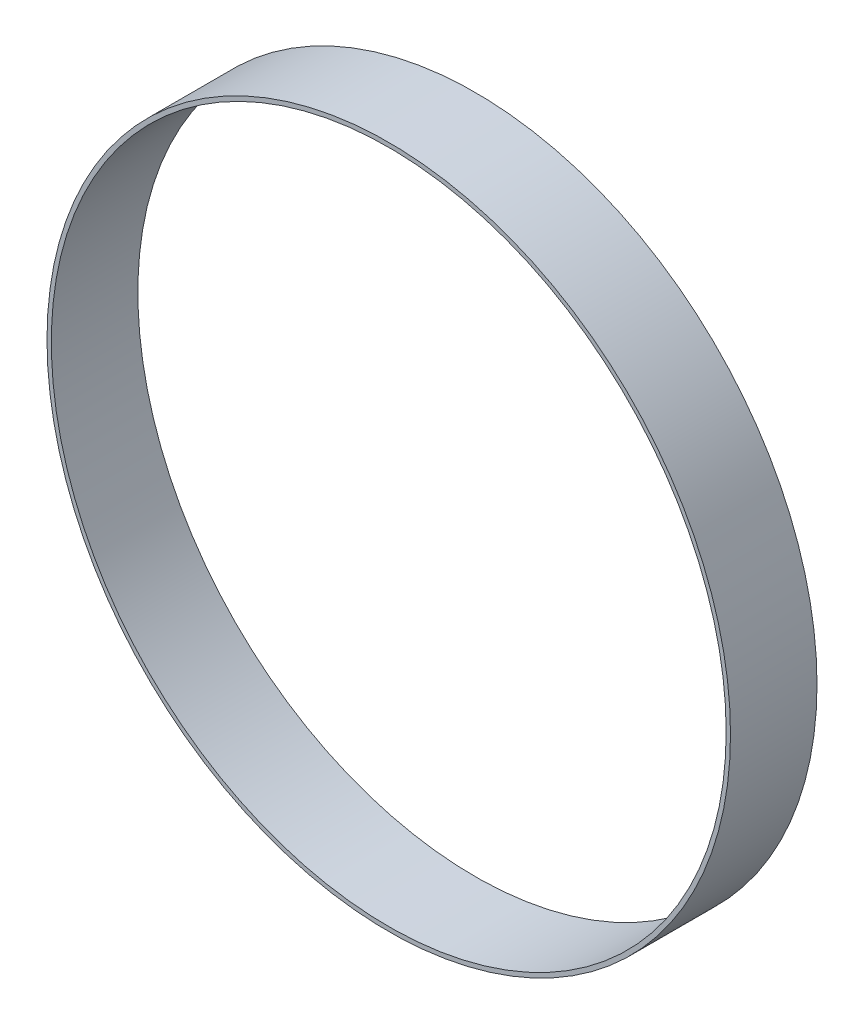
SolidWorks part; units mm, degrees
material "PA Tipo 6"
ref_plane "Alzado" through (0, 0, 0) normal (0, 0, 1) x (1, 0, 0)
ref_plane "Planta" through (0, 0, 0) normal (0, 1, 0) x (1, 0, 0)
ref_plane "Vista lateral" through (0, 0, 0) normal (1, 0, 0) x (0, 0, -1)
sketch "Croquis1" plane through (0, 0, 0) normal (0, 0, 1) x (1, 0, 0)
  line L0 (0, 52.686) -> (0, -52.9587) construction
  circle A4 centre (0, 0) radius 39
  circle A5 centre (0, 0) radius 39.5
  dimension "D1" = 79
  dimension "D2" = 78
extrude "Saliente-Extruir1" add sketch "Croquis1" along normal mid plane 10
